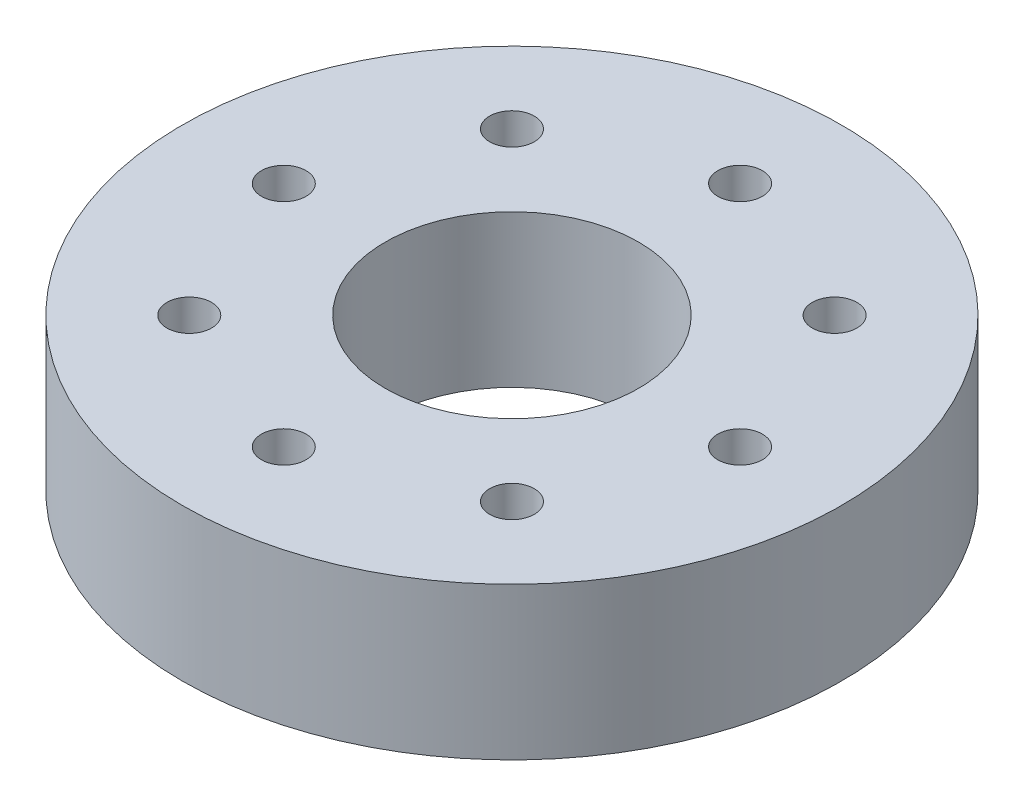
SolidWorks part; units mm, degrees
ref_plane "Front Plane" through (0, 0, 0) normal (0, 0, 1) x (1, 0, 0)
ref_plane "Top Plane" through (0, 0, 0) normal (0, 1, 0) x (1, 0, 0)
ref_plane "Right Plane" through (0, 0, 0) normal (1, 0, 0) x (0, 0, -1)
sketch "Sketch1" plane through (0, 0, 0) normal (0, 1, 0) x (1, 0, 0)
  circle A0 centre (0, 0) radius 32.5
  dimension "D1" = 65
extrude "Boss-Extrude1" add sketch "Sketch1" along normal blind 15
sketch "Sketch2" plane through (0, 15, 0) normal (0, 1, 0) x (1, 0, 0)
  line L0 (0, -55) -> (0, 55) construction
  line L1 (-55, 0) -> (55, 0) construction
  circle A0 centre (0, 22.5) radius 2.2
  circle A1 centre (15.9099, 15.9099) radius 2.2
  circle A2 centre (22.5, 0) radius 2.2
  circle A3 centre (15.9099, -15.9099) radius 2.2
  circle A4 centre (0, -22.5) radius 2.2
  circle A5 centre (-15.9099, -15.9099) radius 2.2
  circle A6 centre (-22.5, 0) radius 2.2
  circle A7 centre (-15.9099, 15.9099) radius 2.2
  point P22 (0, 0)
  dimension "D2" = 4.4
  dimension "D1" = 22.5
  dimension "D3" = 8
extrude "Cut-Extrude1" cut sketch "Sketch2" against normal through all
sketch "Sketch3" plane through (0, 15, 0) normal (0, 1, 0) x (1, 0, 0)
  circle A0 centre (0, 0) radius 12.5
  dimension "D1" = 25
extrude "Cut-Extrude2" cut sketch "Sketch3" against normal through all
